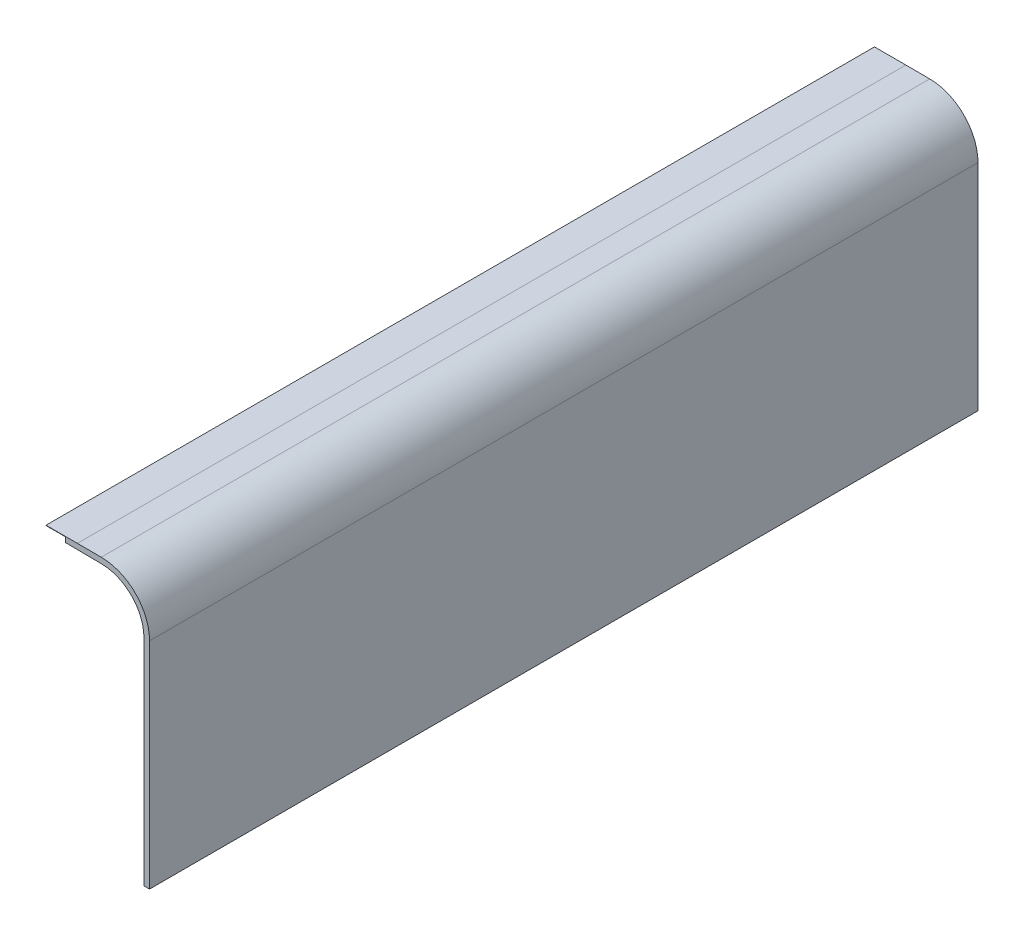
SolidWorks part; units mm, degrees
ref_plane "Front Plane" through (0, 0, 0) normal (0, 0, 1) x (1, 0, 0)
ref_plane "Top Plane" through (0, 0, 0) normal (0, 1, 0) x (1, 0, 0)
ref_plane "Right Plane" through (0, 0, 0) normal (1, 0, 0) x (0, 0, -1)
sketch "Sketch1" plane through (0, 0, 0) normal (0, 0, 1) x (1, 0, 0)
  line L0 (459.7218, -469.9) -> (459.7218, -86.36)
  line L1 (383.5218, -10.16) -> (320.0218, -9.5)
  line L2 (469.7218, -469.9) -> (469.7218, -86.36)
  line L3 (383.5412, -0.16) -> (340.9764, 0)
  line L4 (383.5218, -10.16) -> (340.9388, -9.9999) construction
  line L6 (340.9764, 0) -> (284.9795, 0)
  line L7 (215.8818, 0) -> (320.0218, 0) construction
  line L8 (284.9795, 0) -> (284.9795, -0.6)
  line L9 (284.9795, -0.6) -> (320.0218, -0.6)
  line L10 (320.0218, -9.5) -> (320.0218, 0) construction
  line L11 (320.0218, -0.6) -> (320.0218, -9.5)
  line L12 (459.7218, -469.9) -> (469.7218, -469.9)
  arc A0 (459.7218, -86.36) -> (383.5218, -10.16) centre (383.5218, -86.36) ccw construction
  arc A1 (459.7218, -86.36) -> (383.5218, -10.16) centre (383.5218, -86.36) ccw
  arc A2 (469.7218, -86.36) -> (383.5412, -0.16) centre (383.5218, -86.36) ccw
  dimension "D1" = 10
  dimension "D2" = 0.6
extrude "Boss-Extrude1" add sketch "Sketch1" against normal up to surface (1478.12 mm away)
